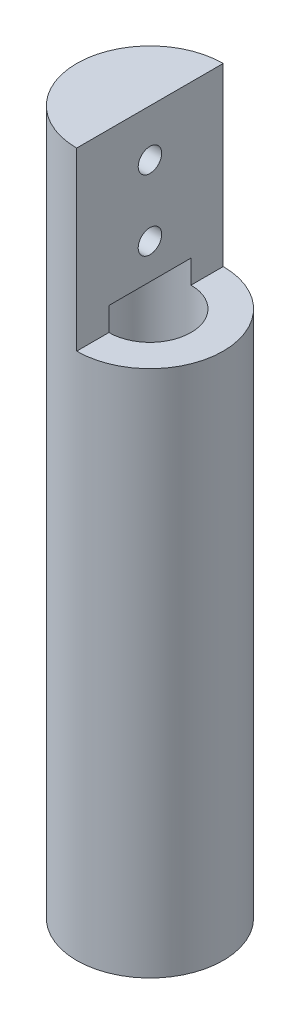
SolidWorks part; units mm, degrees
ref_plane "Front Plane" through (0, 0, 0) normal (0, 0, 1) x (1, 0, 0)
ref_plane "Top Plane" through (0, 0, 0) normal (0, 1, 0) x (1, 0, 0)
ref_plane "Right Plane" through (0, 0, 0) normal (1, 0, 0) x (0, 0, -1)
sketch "Sketch1" plane through (0, 0, 0) normal (0, 1, 0) x (1, 0, 0)
  circle A0 centre (0, 0) radius 6.25
  dimension "D1" = 12.5
extrude "Boss-Extrude1" add sketch "Sketch1" along normal blind 60
sketch "Sketch2" plane through (0, 60, 0) normal (0, 1, 0) x (1, 0, 0)
  line L0 (0, 6.25) -> (0, -6.25)
  circle A0 centre (0, 0) radius 6.25 construction
  arc A1 (0, -6.25) -> (0, 6.25) centre (0, 0) ccw
extrude "Cut-Extrude2" cut sketch "Sketch2" against normal blind 15
sketch "Sketch3" plane through (0, 45, 0) normal (0, 1, 0) x (1, 0, 0)
  circle A0 centre (0, 0) radius 3.5
  dimension "D1" = 7
extrude "Cut-Extrude3" cut sketch "Sketch3" against normal through all
sketch "Sketch7" plane through (0, 45, 0) normal (0, -1, 0) x (1, 0, 0)
  circle A0 centre (0, 0) radius 3.5
  dimension "D1" = 7
extrude "Cut-Extrude5" cut sketch "Sketch7" against normal blind 2
sketch "Sketch8" plane through (0, 0, 0) normal (1, 0, 0) x (0, 0, -1)
  line L0 (6.25, 60) -> (-6.25, 60) construction
  circle A0 centre (0, 56) radius 1
  dimension "D1" = 2
  dimension "D2" = 4
extrude "Cut-Extrude6" cut sketch "Sketch8" against normal through all
pattern_linear "LPattern1" count 2 spacing 6 along (0, -1, 0) of "Cut-Extrude6"
sketch "Sketch9" plane through (0, 0, 0) normal (0, -1, 0) x (1, 0, 0)
  circle A0 centre (-4.5, 0) radius 0.75
  dimension "D1" = 1.5
  dimension "D2" = 4.5
extrude "Cut-Extrude7" cut sketch "Sketch9" against normal blind 5
pattern_circular "CirPattern1" count 2 over 360 about axis through (0, 0, 0) along (0, 1, 0) of "Cut-Extrude7"
